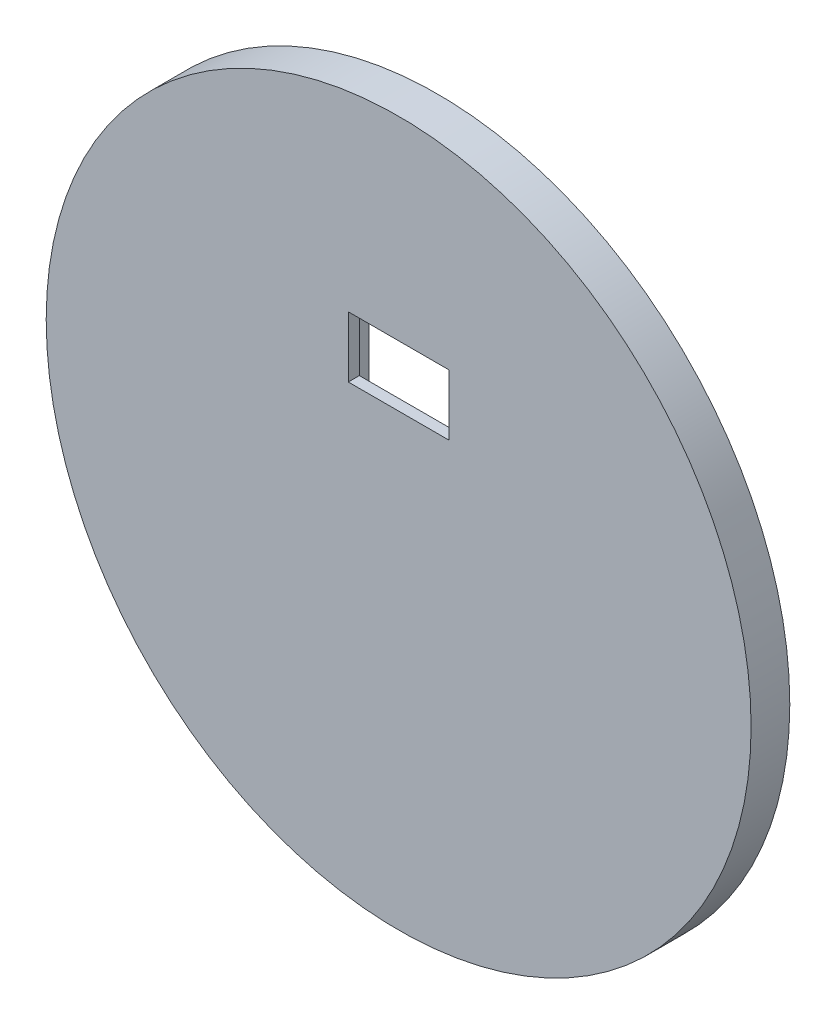
SolidWorks part; units mm, degrees
ref_plane "Front Plane" through (0, 0, 0) normal (0, 0, 1) x (1, 0, 0)
ref_plane "Top Plane" through (0, 0, 0) normal (0, 1, 0) x (1, 0, 0)
ref_plane "Right Plane" through (0, 0, 0) normal (1, 0, 0) x (0, 0, -1)
sketch "Sketch1" plane through (0, 0, 0) normal (0, 0, 1) x (1, 0, 0)
  circle A0 centre (0, 0) radius 63.76
extrude "Boss-Extrude1" add sketch "Sketch1" along normal blind 7
sketch "Sketch4" plane through (0, 0, 0) normal (0, 0, -1) x (-1, 0, 0)
  line L1 (-12.4, 32.91) -> (12.4, 32.91)
  line L2 (-12.4, 32.91) -> (-12.4, -12.42)
  line L3 (-12.4, -12.42) -> (12.4, -12.42)
  line L4 (12.4, 32.91) -> (12.4, -12.42)
  dimension "D1" = 12.42
  dimension "D2" = 32.91
  dimension "D3" = 12.4
  dimension "D4" = 12.4
extrude "Cut-Extrude1" cut sketch "Sketch4" against normal blind 5
fillet "Fillet1" radius 6.35 4 edges at (12.4, 32.91, 2.5) (-12.4, 32.91, 2.5) (12.4, -12.42, 2.5) (-12.4, -12.42, 2.5)
sketch "Sketch5" plane through (0, 0, 5) normal (0, 0, -1) x (-1, 0, 0)
  line L1 (-9.112, 28.5654) -> (9.112, 28.5654)
  line L2 (-9.112, 28.5654) -> (-9.112, 17.5606)
  line L3 (-9.112, 17.5606) -> (9.112, 17.5606)
  line L4 (9.112, 28.5654) -> (9.112, 17.5606)
  line L5 (-9.112, 28.5654) -> (9.112, 17.5606) construction
  line L6 (-9.112, 17.5606) -> (9.112, 28.5654) construction
  point P0 (0, 23.063)
extrude "Cut-Extrude2" cut sketch "Sketch5" against normal up to next
